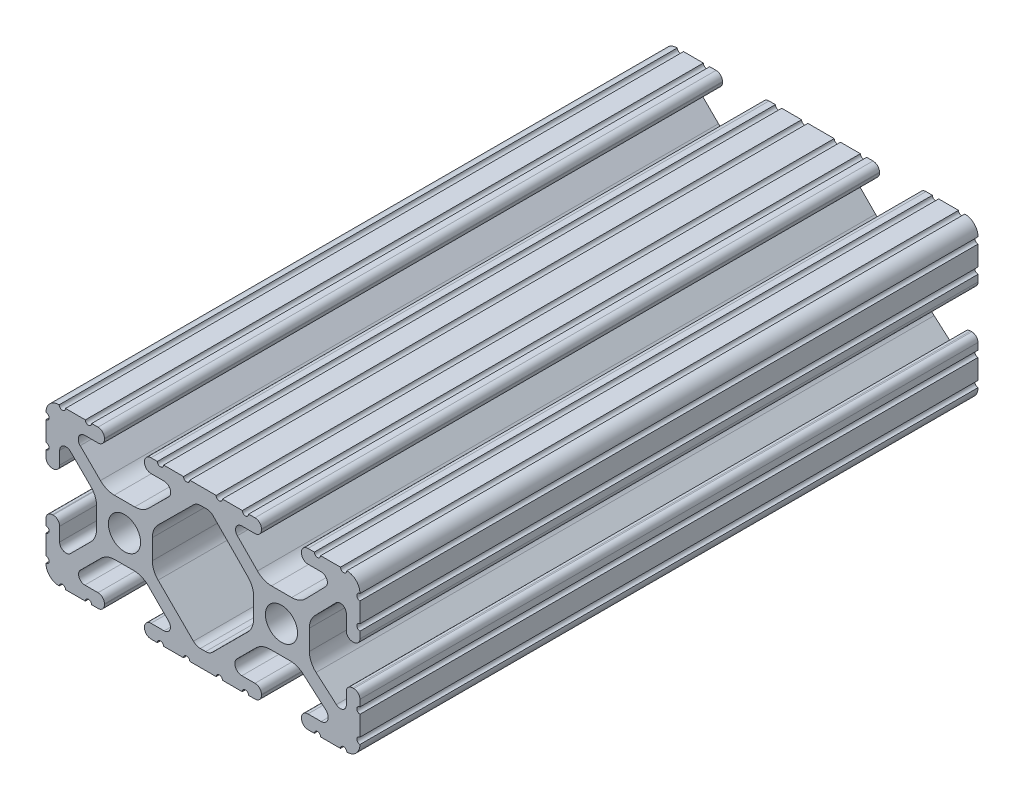
SolidWorks part; units mm, degrees
ref_plane "Front Plane" through (0, 0, 0) normal (0, 0, 1) x (1, 0, 0)
ref_plane "Top Plane" through (0, 0, 0) normal (0, 1, 0) x (1, 0, 0)
ref_plane "Right Plane" through (0, 0, 0) normal (1, 0, 0) x (0, 0, -1)
sketch "Sketch1" plane through (0, 0, 0) normal (0, 0, 1) x (1, 0, 0)
  line L0 (-7.2595, -3.8694) -> (-1.5457, -9.5728)
  line L1 (-8.1915, 1.6223) -> (-8.1915, -1.6223)
  line L2 (-1.504, 9.5765) -> (-7.252, 3.8768)
  line L3 (0.5515, 10.033) -> (-0.3952, 10.033)
  line L4 (7.2829, 3.8459) -> (1.6756, 9.5611)
  line L5 (8.1915, -1.6223) -> (8.1915, 1.6223)
  line L6 (1.5457, -9.5728) -> (7.2595, -3.8694)
  line L7 (-0.4332, -10.033) -> (0.4332, -10.033)
  line L8 (18.0171, 12.7) -> (16.9875, 12.7)
  line L9 (15.9385, 11.651) -> (15.9385, 11.5392)
  line L10 (16.9875, 10.4902) -> (19.1164, 10.4902)
  line L11 (19.8441, 8.7652) -> (16.619, 5.4551)
  line L12 (14.3449, 4.4958) -> (11.0833, 4.4958)
  line L13 (8.817, 5.4472) -> (5.5642, 8.7627)
  line L14 (6.2894, 10.4902) -> (8.4125, 10.4902)
  line L15 (9.4615, 11.5392) -> (9.4615, 11.651)
  line L16 (8.4125, 12.7) -> (7.3829, 12.7)
  line L17 (6.3669, 12.7) -> (3.1496, 12.7)
  line L18 (2.1336, 12.7) -> (-2.1336, 12.7)
  line L19 (-3.1496, 12.7) -> (-6.3669, 12.7)
  line L20 (-7.3829, 12.7) -> (-8.4125, 12.7)
  line L21 (-9.4615, 11.651) -> (-9.4615, 11.5392)
  line L22 (-8.4125, 10.4902) -> (-6.2836, 10.4902)
  line L23 (-5.5326, 8.6661) -> (-8.81, 5.4163)
  line L24 (-11.0455, 4.4958) -> (-14.3545, 4.4958)
  line L25 (-16.59, 5.4163) -> (-19.8674, 8.6661)
  line L26 (-19.1164, 10.4902) -> (-16.9875, 10.4902)
  line L27 (-15.9385, 11.5392) -> (-15.9385, 11.651)
  line L28 (-16.9875, 12.7) -> (-18.0171, 12.7)
  line L29 (-19.0331, 12.7) -> (-22.2504, 12.7)
  line L30 (-25.4, 9.5504) -> (-25.4, 6.3331)
  line L31 (-25.4, 5.3171) -> (-25.4, 4.2375)
  line L32 (-24.401, 3.2385) -> (-24.2392, 3.2385)
  line L33 (-23.1902, 4.2875) -> (-23.1902, 6.3347)
  line L34 (-21.434, 7.0665) -> (-18.148, 3.8082)
  line L35 (-17.2085, 1.5536) -> (-17.2085, -1.6952)
  line L36 (-18.1405, -3.9423) -> (-21.4316, -7.2274)
  line L37 (-23.1902, -6.498) -> (-23.1902, -4.2875)
  line L38 (-24.2392, -3.2385) -> (-24.351, -3.2385)
  line L39 (-25.4, -4.2875) -> (-25.4, -5.3171)
  line L40 (-25.4, -6.3331) -> (-25.4, -9.5504)
  line L41 (-22.2504, -12.7) -> (-19.0331, -12.7)
  line L42 (-18.0171, -12.7) -> (-16.9875, -12.7)
  line L43 (-15.9384, -11.651) -> (-15.9384, -11.5392)
  line L44 (-16.9875, -10.4902) -> (-19.1164, -10.4902)
  line L45 (-19.8341, -8.7551) -> (-16.4966, -5.4237)
  line L46 (-14.2536, -4.4958) -> (-11.1464, -4.4958)
  line L47 (-8.9034, -5.4237) -> (-5.5659, -8.7551)
  line L48 (-6.2836, -10.4902) -> (-8.4125, -10.4902)
  line L49 (-9.4616, -11.5392) -> (-9.4616, -11.651)
  line L50 (-8.4125, -12.7) -> (-7.3829, -12.7)
  line L51 (-6.3669, -12.7) -> (-3.1496, -12.7)
  line L52 (-2.1336, -12.7) -> (2.1336, -12.7)
  line L53 (3.1496, -12.7) -> (6.3669, -12.7)
  line L54 (7.3829, -12.7) -> (8.4125, -12.7)
  line L55 (9.4616, -11.651) -> (9.4616, -11.5392)
  line L56 (8.4125, -10.4902) -> (6.2894, -10.4902)
  line L57 (5.4807, -8.5353) -> (8.5979, -5.4237)
  line L58 (10.8409, -4.4958) -> (14.1026, -4.4958)
  line L59 (16.1879, -5.2766) -> (19.8682, -8.4822)
  line L60 (19.1164, -10.4902) -> (16.9875, -10.4902)
  line L61 (15.9384, -11.5392) -> (15.9384, -11.651)
  line L62 (16.9875, -12.7) -> (18.0171, -12.7)
  line L63 (19.0331, -12.7) -> (22.2504, -12.7)
  line L64 (25.4, -9.5504) -> (25.4, -6.3331)
  line L65 (25.4, -5.3171) -> (25.4, -4.2375)
  line L66 (24.401, -3.2385) -> (24.1892, -3.2385)
  line L67 (23.1902, -4.2375) -> (23.1902, -6.1559)
  line L68 (21.584, -6.8869) -> (18.2982, -4.025)
  line L69 (17.2085, -1.6308) -> (17.2085, 1.6308)
  line L70 (18.1094, 3.8465) -> (21.5263, 7.3534)
  line L71 (23.1902, 6.6769) -> (23.1902, 4.2375)
  line L72 (24.1892, 3.2385) -> (24.401, 3.2385)
  line L73 (25.4, 4.2375) -> (25.4, 5.3171)
  line L74 (25.4, 6.3332) -> (25.4, 9.5504)
  line L75 (22.2504, 12.7) -> (19.0331, 12.7)
  circle A0 centre (-12.7, 0) radius 2.6035
  circle A1 centre (12.7, 0) radius 2.6035
  arc A2 (-1.5457, -9.5728) -> (-0.4332, -10.033) centre (-0.4332, -8.4582) ccw
  arc A3 (-8.1915, -1.6223) -> (-7.2595, -3.8694) centre (-5.0165, -1.6223) ccw
  arc A4 (-7.252, 3.8768) -> (-8.1915, 1.6223) centre (-5.0165, 1.6223) ccw
  arc A5 (-0.3952, 10.033) -> (-1.504, 9.5765) centre (-0.3952, 8.4582) ccw
  arc A6 (1.6756, 9.5611) -> (0.5515, 10.033) centre (0.5515, 8.4582) ccw
  arc A7 (8.1915, 1.6223) -> (7.2829, 3.8459) centre (5.0165, 1.6223) ccw
  arc A8 (7.2595, -3.8694) -> (8.1915, -1.6223) centre (5.0165, -1.6223) ccw
  arc A9 (0.4332, -10.033) -> (1.5457, -9.5728) centre (0.4332, -8.4582) ccw
  arc A10 (18.0171, 12.7) -> (19.0331, 12.7) centre (18.5251, 12.7) ccw
  arc A11 (16.9875, 12.7) -> (15.9385, 11.651) centre (16.9875, 11.651) ccw
  arc A12 (15.9385, 11.5392) -> (16.9875, 10.4902) centre (16.9875, 11.5392) ccw
  arc A13 (19.8441, 8.7652) -> (19.1164, 10.4902) centre (19.1164, 9.4742) ccw
  arc A14 (14.3449, 4.4958) -> (16.619, 5.4551) centre (14.3449, 7.6708) ccw
  arc A15 (8.817, 5.4472) -> (11.0833, 4.4958) centre (11.0833, 7.6708) ccw
  arc A16 (6.2894, 10.4902) -> (5.5642, 8.7627) centre (6.2894, 9.4742) ccw
  arc A17 (8.4125, 10.4902) -> (9.4615, 11.5392) centre (8.4125, 11.5392) ccw
  arc A18 (9.4615, 11.651) -> (8.4125, 12.7) centre (8.4125, 11.651) ccw
  arc A19 (6.3669, 12.7) -> (7.3829, 12.7) centre (6.8749, 12.7) ccw
  arc A20 (2.1336, 12.7) -> (3.1496, 12.7) centre (2.6416, 12.7) ccw
  arc A21 (-3.1496, 12.7) -> (-2.1336, 12.7) centre (-2.6416, 12.7) ccw
  arc A22 (-7.3829, 12.7) -> (-6.3669, 12.7) centre (-6.8749, 12.7) ccw
  arc A23 (-8.4125, 12.7) -> (-9.4615, 11.651) centre (-8.4125, 11.651) ccw
  arc A24 (-9.4615, 11.5392) -> (-8.4125, 10.4902) centre (-8.4125, 11.5392) ccw
  arc A25 (-5.5326, 8.6661) -> (-6.2836, 10.4902) centre (-6.2836, 9.4235) ccw
  arc A26 (-11.0455, 4.4958) -> (-8.81, 5.4163) centre (-11.0455, 7.6708) ccw
  arc A27 (-16.59, 5.4163) -> (-14.3545, 4.4958) centre (-14.3545, 7.6708) ccw
  arc A28 (-19.1164, 10.4902) -> (-19.8674, 8.6661) centre (-19.1164, 9.4235) ccw
  arc A29 (-16.9875, 10.4902) -> (-15.9385, 11.5392) centre (-16.9875, 11.5392) ccw
  arc A30 (-15.9385, 11.651) -> (-16.9875, 12.7) centre (-16.9875, 11.651) ccw
  arc A31 (-19.0331, 12.7) -> (-18.0171, 12.7) centre (-18.5251, 12.7) ccw
  arc A32 (-23.2664, 12.6998) -> (-22.2504, 12.7) centre (-22.7584, 12.7) ccw
  arc A33 (-23.2664, 12.6998) -> (-25.3998, 10.5664) centre (-23.2918, 10.5918) ccw
  arc A34 (-25.4, 9.5504) -> (-25.3998, 10.5664) centre (-25.4, 10.0584) ccw
  arc A35 (-25.4, 5.3171) -> (-25.4, 6.3331) centre (-25.4, 5.8251) ccw
  arc A36 (-25.4, 4.2375) -> (-24.401, 3.2385) centre (-24.401, 4.2375) ccw
  arc A37 (-24.2392, 3.2385) -> (-23.1902, 4.2875) centre (-24.2392, 4.2875) ccw
  arc A38 (-21.434, 7.0665) -> (-23.1902, 6.3347) centre (-22.1596, 6.3347) ccw
  arc A39 (-17.2085, 1.5536) -> (-18.148, 3.8082) centre (-20.3835, 1.5536) ccw
  arc A40 (-18.1405, -3.9423) -> (-17.2085, -1.6952) centre (-20.3835, -1.6952) ccw
  arc A41 (-23.1902, -6.498) -> (-21.4316, -7.2274) centre (-22.1596, -6.498) ccw
  arc A42 (-23.1902, -4.2875) -> (-24.2392, -3.2385) centre (-24.2392, -4.2875) ccw
  arc A43 (-24.351, -3.2385) -> (-25.4, -4.2875) centre (-24.351, -4.2875) ccw
  arc A44 (-25.4, -6.3331) -> (-25.4, -5.3171) centre (-25.4, -5.8251) ccw
  arc A45 (-25.3998, -10.5664) -> (-25.4, -9.5504) centre (-25.4, -10.0584) ccw
  arc A46 (-25.3998, -10.5664) -> (-23.2664, -12.6998) centre (-23.2918, -10.5918) ccw
  arc A47 (-22.2504, -12.7) -> (-23.2664, -12.6998) centre (-22.7584, -12.7) ccw
  arc A48 (-18.0171, -12.7) -> (-19.0331, -12.7) centre (-18.5251, -12.7) ccw
  arc A49 (-16.9875, -12.7) -> (-15.9384, -11.651) centre (-16.9875, -11.651) ccw
  arc A50 (-15.9384, -11.5392) -> (-16.9875, -10.4902) centre (-16.9875, -11.5392) ccw
  arc A51 (-19.8341, -8.7551) -> (-19.1164, -10.4902) centre (-19.1164, -9.4742) ccw
  arc A52 (-14.2536, -4.4958) -> (-16.4966, -5.4237) centre (-14.2536, -7.6708) ccw
  arc A53 (-8.9034, -5.4237) -> (-11.1464, -4.4958) centre (-11.1464, -7.6708) ccw
  arc A54 (-6.2836, -10.4902) -> (-5.5659, -8.7551) centre (-6.2836, -9.4742) ccw
  arc A55 (-8.4125, -10.4902) -> (-9.4616, -11.5392) centre (-8.4125, -11.5392) ccw
  arc A56 (-9.4616, -11.651) -> (-8.4125, -12.7) centre (-8.4125, -11.651) ccw
  arc A57 (-6.3669, -12.7) -> (-7.3829, -12.7) centre (-6.8749, -12.7) ccw
  arc A58 (-2.1336, -12.7) -> (-3.1496, -12.7) centre (-2.6416, -12.7) ccw
  arc A59 (3.1496, -12.7) -> (2.1336, -12.7) centre (2.6416, -12.7) ccw
  arc A60 (7.3829, -12.7) -> (6.3669, -12.7) centre (6.8749, -12.7) ccw
  arc A61 (8.4125, -12.7) -> (9.4616, -11.651) centre (8.4125, -11.651) ccw
  arc A62 (9.4616, -11.5392) -> (8.4125, -10.4902) centre (8.4125, -11.5392) ccw
  arc A63 (5.4807, -8.5353) -> (6.2894, -10.4902) centre (6.2894, -9.3455) ccw
  arc A64 (10.8409, -4.4958) -> (8.5979, -5.4237) centre (10.8409, -7.6708) ccw
  arc A65 (16.1879, -5.2766) -> (14.1026, -4.4958) centre (14.1026, -7.6708) ccw
  arc A66 (19.1164, -10.4902) -> (19.8682, -8.4822) centre (19.1164, -9.3455) ccw
  arc A67 (16.9875, -10.4902) -> (15.9384, -11.5392) centre (16.9875, -11.5392) ccw
  arc A68 (15.9384, -11.651) -> (16.9875, -12.7) centre (16.9875, -11.651) ccw
  arc A69 (19.0331, -12.7) -> (18.0171, -12.7) centre (18.5251, -12.7) ccw
  arc A70 (23.2664, -12.6998) -> (22.2504, -12.7) centre (22.7584, -12.7) ccw
  arc A71 (23.2664, -12.6998) -> (25.3998, -10.5664) centre (23.2918, -10.5918) ccw
  arc A72 (25.4, -9.5504) -> (25.3998, -10.5664) centre (25.4, -10.0584) ccw
  arc A73 (25.4, -5.3171) -> (25.4, -6.3331) centre (25.4, -5.8251) ccw
  arc A74 (25.4, -4.2375) -> (24.401, -3.2385) centre (24.401, -4.2375) ccw
  arc A75 (24.1892, -3.2385) -> (23.1902, -4.2375) centre (24.1892, -4.2375) ccw
  arc A76 (21.584, -6.8869) -> (23.1902, -6.1559) centre (22.2207, -6.1559) ccw
  arc A77 (17.2085, -1.6308) -> (18.2982, -4.025) centre (20.3835, -1.6308) ccw
  arc A78 (18.1094, 3.8465) -> (17.2085, 1.6308) centre (20.3835, 1.6308) ccw
  arc A79 (23.1902, 6.6769) -> (21.5263, 7.3534) centre (22.2207, 6.6769) ccw
  arc A80 (23.1902, 4.2375) -> (24.1892, 3.2385) centre (24.1892, 4.2375) ccw
  arc A81 (24.401, 3.2385) -> (25.4, 4.2375) centre (24.401, 4.2375) ccw
  arc A82 (25.4, 6.3332) -> (25.4, 5.3171) centre (25.4, 5.8251) ccw
  arc A83 (25.3998, 10.5664) -> (25.4, 9.5504) centre (25.4, 10.0584) ccw
  arc A84 (25.3998, 10.5664) -> (23.2664, 12.6998) centre (23.2918, 10.5918) ccw
  arc A85 (22.2504, 12.7) -> (23.2664, 12.6998) centre (22.7584, 12.7) ccw
  point P248 (0, 10.033)
extrude "Boss-Extrude1" add sketch "Sketch1" along normal mid plane 100
